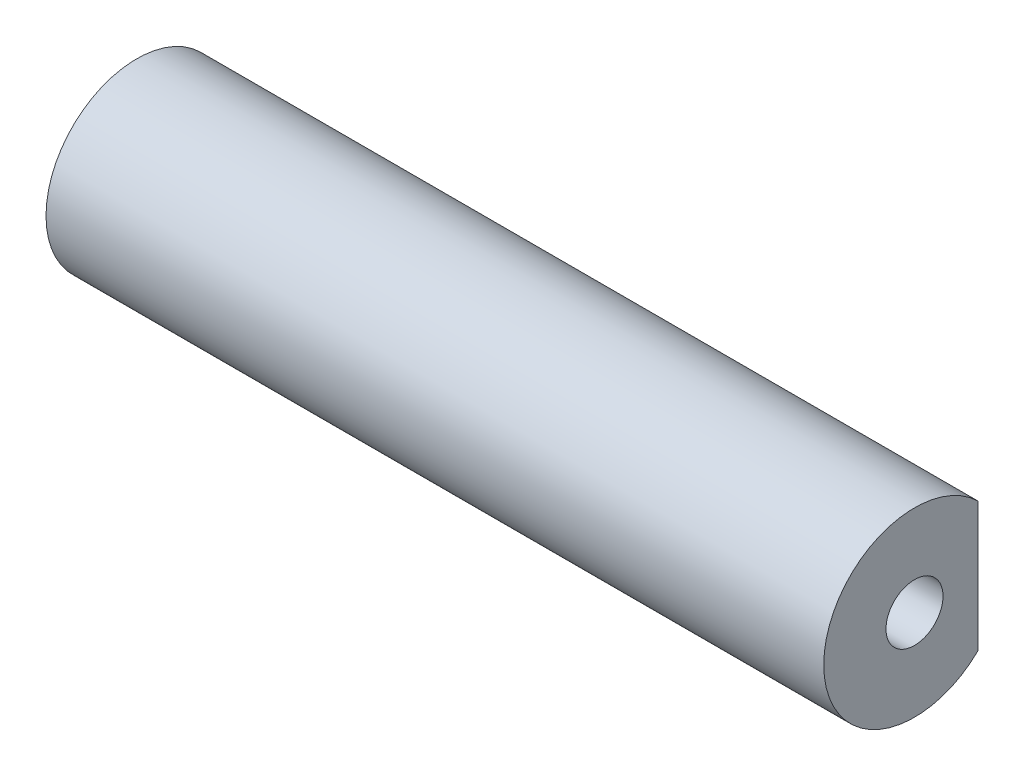
SolidWorks part; units mm, degrees
ref_plane "Front Plane" through (0, 0, 0) normal (0, 0, 1) x (1, 0, 0)
ref_plane "Top Plane" through (0, 0, 0) normal (0, 1, 0) x (1, 0, 0)
ref_plane "Right Plane" through (0, 0, 0) normal (1, 0, 0) x (0, 0, -1)
sketch "Sketch1" plane through (0, 0, 0) normal (1, 0, 0) x (0, 0, -1)
  circle A0 centre (0, 0) radius 3.5
  dimension "D1" = 7
extrude "Boss-Extrude1" add sketch "Sketch1" along normal blind 30
sketch "Sketch2" plane through (0, 0, 0) normal (-1, 0, 0) x (0, 0, 1)
  circle A0 centre (0, 0) radius 1.2
  dimension "D1" = 2.4
extrude "Cut-Extrude1" cut sketch "Sketch2" against normal blind 15
sketch "Sketch3" plane through (30, 0, 0) normal (1, 0, 0) x (0, 0, -1)
  circle A0 centre (0, 0) radius 1.1
  dimension "D1" = 2.2
extrude "Cut-Extrude2" cut sketch "Sketch3" against normal blind 15
sketch "Sketch4" plane through (30, 0, 0) normal (1, 0, 0) x (0, 0, -1)
  line L0 (2.4495, 2.5) -> (2.4495, -2.5)
  circle A0 centre (0, 0) radius 3.5 construction
  arc A1 (2.4495, 2.5) -> (2.4495, -2.5) centre (0, 0) cw
  point P5 (2.4495, 2.5)
  point P6 (2.4495, -2.5)
  dimension "D1" = 5
extrude "Cut-Extrude3" cut sketch "Sketch4" against normal up to surface (30 mm away) up to face at (0, 0, 1.2)
